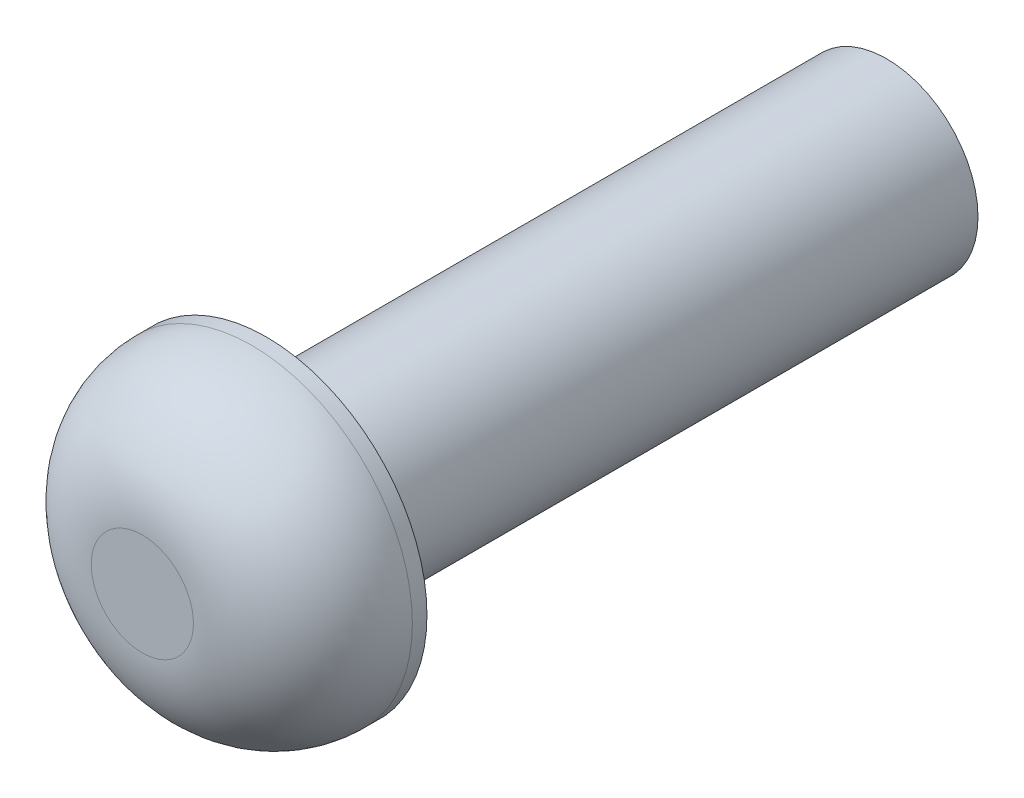
SolidWorks part; units mm, degrees
ref_plane "前视基准面" through (0, 0, 0) normal (0, 0, 1) x (1, 0, 0)
ref_plane "上视基准面" through (0, 0, 0) normal (0, 1, 0) x (1, 0, 0)
ref_plane "右视基准面" through (0, 0, 0) normal (1, 0, 0) x (0, 0, -1)
sketch "草图1" plane through (0, 0, 0) normal (0, 0, 1) x (1, 0, 0)
  circle A0 centre (0, 0) radius 2.5
extrude "凸台-拉伸1" add sketch "草图1" along normal blind 17
sketch "草图2" plane through (0, 0, 17) normal (0, 0, 1) x (1, 0, 0)
  circle A0 centre (0, 0) radius 4.4
extrude "凸台-拉伸2" add sketch "草图2" along normal blind 3.4
fillet "圆角1" radius 3 1 edges at (4.4, 0, 20.4)
